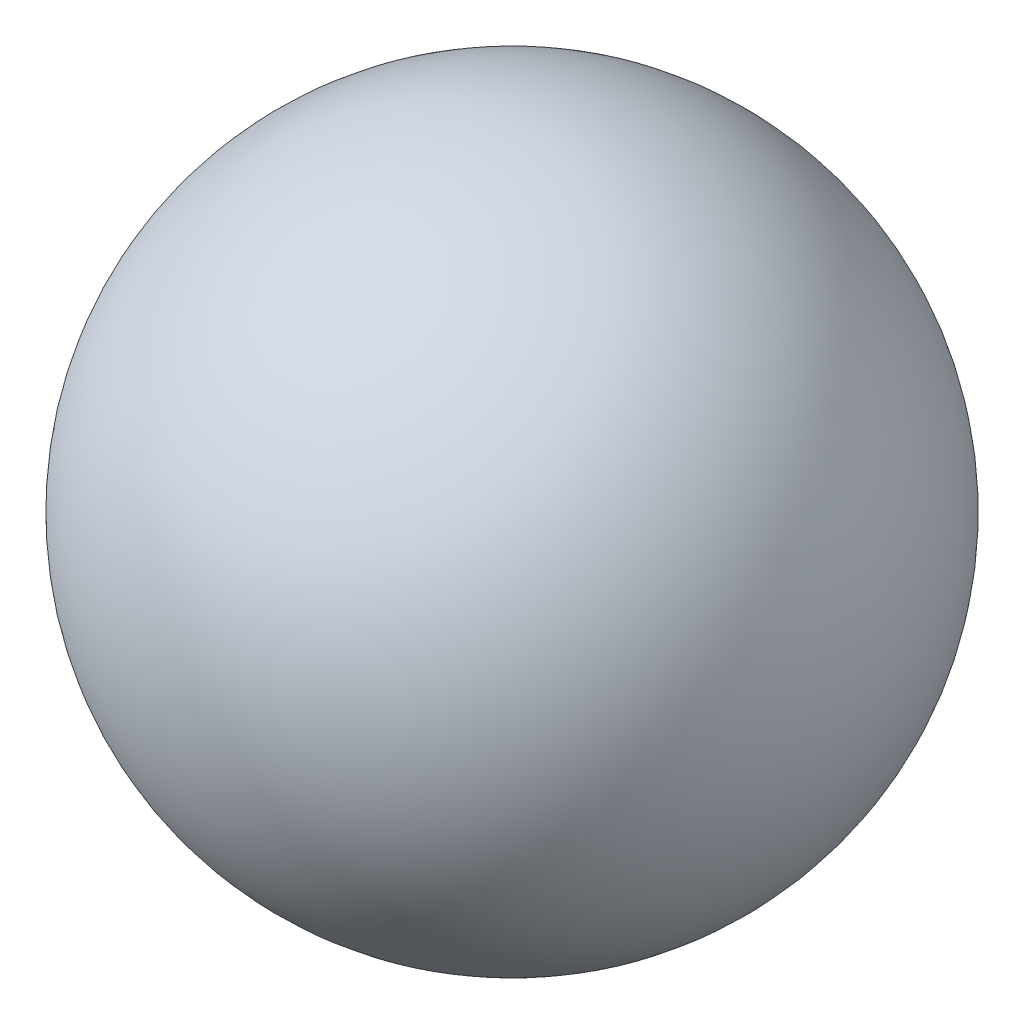
SolidWorks part; units mm, degrees
ref_plane "Plan de face" through (0, 0, 0) normal (0, 0, 1) x (1, 0, 0)
ref_plane "Plan de dessus" through (0, 0, 0) normal (0, 1, 0) x (1, 0, 0)
ref_plane "Plan de droite" through (0, 0, 0) normal (1, 0, 0) x (0, 0, -1)
sketch "Esquisse1" plane through (0, 0, 0) normal (0, 0, 1) x (1, 0, 0)
  line L0 (2, 4) -> (2, 1.5) construction
  line L1 (0.15, 4) -> (3.85, 4) construction
  line L2 (0, 3.85) -> (0, 1.65) construction
  line L3 (0.15, 1.5) -> (3.85, 1.5) construction
  line L4 (4, 3.85) -> (4, 1.65) construction
  line L5 (4, 3.2) -> (0, 3.2) construction
  line L6 (4, 2.3) -> (0, 2.3) construction
  line L7 (0, 0) -> (4, 0) construction
  line L8 (2, 3.7) -> (2, 1.8)
  arc A1 (0, 1.65) -> (0.15, 1.5) centre (0.15, 1.65) ccw construction
  arc A2 (0.15, 4) -> (0, 3.85) centre (0.15, 3.85) ccw construction
  arc A3 (4, 3.85) -> (3.85, 4) centre (3.85, 3.85) ccw construction
  arc A4 (3.85, 1.5) -> (4, 1.65) centre (3.85, 1.65) ccw construction
  arc A5 (2, 3.7) -> (2, 1.8) centre (2, 2.75) ccw
  dimension "D4" = 0.15
  dimension "D5" = 1.9
  dimension "D1" = 1.5
  dimension "D2" = 4
  dimension "D3" = 4
  dimension "D6" = 2.3
  dimension "D7" = 3.2
revolve "Révolution1" add sketch "Esquisse1" angle 360 about L0
